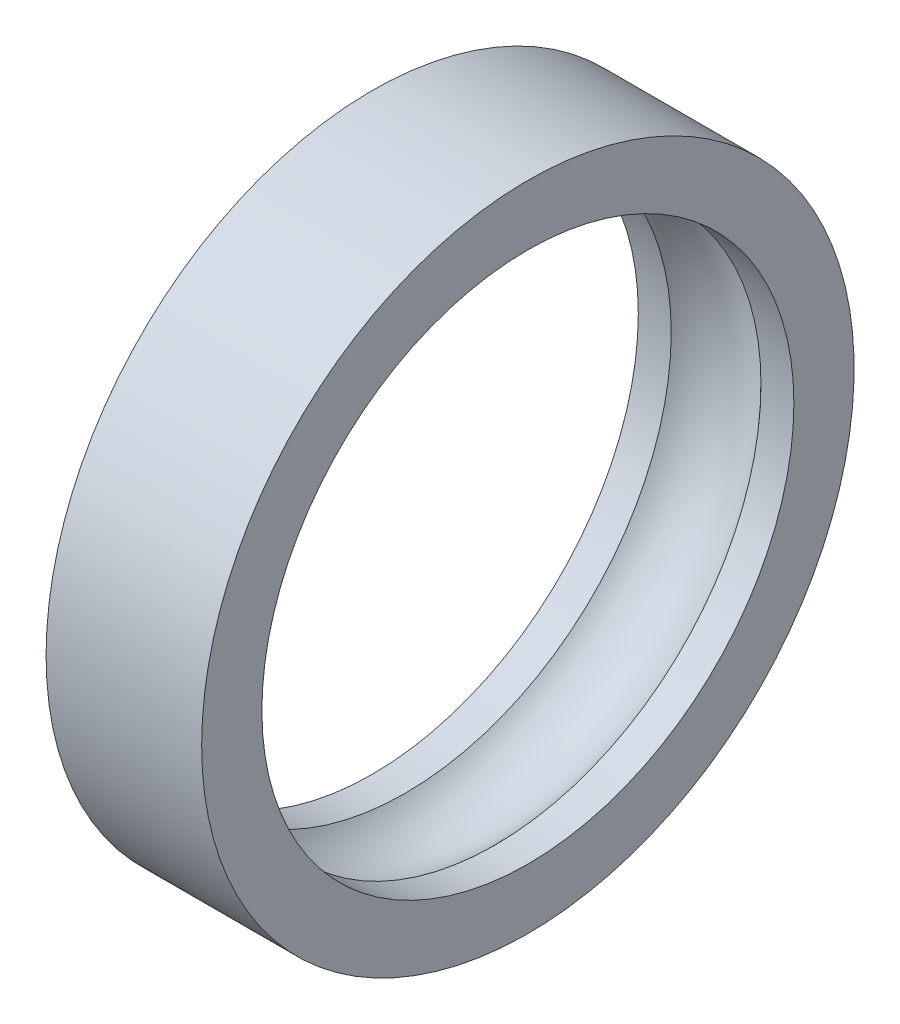
SolidWorks part; units mm, degrees
ref_plane "Front Plane" through (0, 0, 0) normal (0, 0, 1) x (1, 0, 0)
ref_plane "Top Plane" through (0, 0, 0) normal (0, 1, 0) x (1, 0, 0)
ref_plane "Right Plane" through (0, 0, 0) normal (1, 0, 0) x (0, 0, -1)
sketch "Sketch1" plane through (0, 0, 0) normal (0, 0, 1) x (1, 0, 0)
  line L0 (0, 0) -> (10396.4434, 0) construction
  line L1 (4.4721, 26.5) -> (7.75, 26.5)
  line L2 (-7.75, 32.5) -> (7.75, 32.5)
  line L3 (-7.75, 32.5) -> (-7.75, 26.5)
  line L4 (-7.75, 26.5) -> (-4.4721, 26.5)
  line L5 (7.75, 32.5) -> (7.75, 26.5)
  line L6 (-7.75, 32.5) -> (7.75, 26.5) construction
  line L7 (-7.75, 26.5) -> (7.75, 32.5) construction
  arc A0 (4.4721, 26.5) -> (-4.4721, 26.5) centre (0, 22.5) ccw
  point P3 (0, 29.5)
  dimension "D3" = 12
  dimension "D1" = 15.5
  dimension "D2" = 32.5
  dimension "D4" = 4
  dimension "D5" = 26.5
revolve "Revolve1" add sketch "Sketch1" angle 360 about L0
